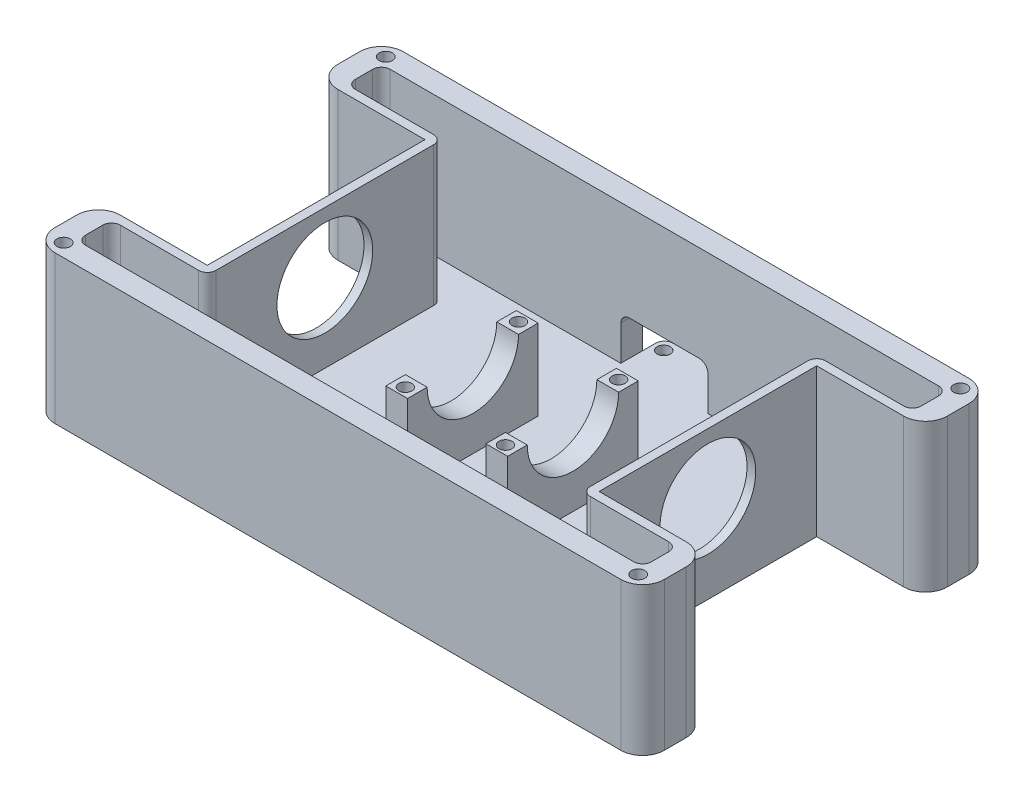
SolidWorks part; units mm, degrees
ref_plane "Front Plane" through (0, 0, 0) normal (0, 0, 1) x (1, 0, 0)
ref_plane "Top Plane" through (0, 0, 0) normal (0, 1, 0) x (1, 0, 0)
ref_plane "Right Plane" through (0, 0, 0) normal (1, 0, 0) x (0, 0, -1)
sketch "Sketch1" plane through (0, 0, 0) normal (0, 1, 0) x (1, 0, 0)
  line L5 (-88.9, 50.8) -> (88.9, 50.8)
  line L6 (-88.9, 50.8) -> (-88.9, -50.8)
  line L7 (-88.9, -50.8) -> (88.9, -50.8)
  line L8 (88.9, 50.8) -> (88.9, -50.8)
  line L9 (-88.9, 50.8) -> (88.9, -50.8) construction
  line L10 (-88.9, -50.8) -> (88.9, 50.8) construction
  point P0 (0, 0)
  point P1 (0, 0)
  dimension "D1" = 177.8
  dimension "D2" = 101.6
extrude "Boss-Extrude1" add sketch "Sketch1" along normal blind 2.54
sketch "Sketch2" plane through (0, 2.54, 0) normal (0, 1, 0) x (1, 0, 0)
  line L0 (0, 50.8) -> (0, 11.3567) construction
  line L1 (-82.55, 31.75) -> (-57.15, 31.75)
  line L2 (-82.55, 31.75) -> (-82.55, -31.75)
  line L3 (-82.55, -31.75) -> (-57.15, -31.75)
  line L4 (-57.15, 31.75) -> (-57.15, -31.75)
  line L5 (88.9, 50.8) -> (-88.9, 50.8) construction
  line L6 (-88.9, 50.8) -> (-88.9, -50.8) construction
  line L7 (-88.9, -50.8) -> (88.9, -50.8) construction
  line L8 (82.55, -31.75) -> (57.15, -31.75)
  line L9 (82.55, 31.75) -> (82.55, -31.75)
  line L10 (82.55, 31.75) -> (57.15, 31.75)
  line L11 (57.15, 31.75) -> (57.15, -31.75)
  dimension "D1" = 6.35
  dimension "D2" = 25.4
  dimension "D3" = 63.5
  dimension "D4" = 19.05
extrude "Cut-Extrude1" cut sketch "Sketch2" against normal blind 2.54
sketch "Sketch3" plane through (0, 2.54, 0) normal (0, 1, 0) x (1, 0, 0)
  line L51 (-82.55, -44.45) -> (82.55, -44.45)
  line L52 (82.55, -44.45) -> (82.55, 44.45)
  line L53 (82.55, 44.45) -> (-82.55, 44.45)
  line L54 (-82.55, 44.45) -> (-82.55, -44.45)
  line L61 (-88.9, 50.8) -> (-88.9, -50.8)
  line L62 (88.9, -50.8) -> (88.9, 50.8)
  line L63 (-88.9, -50.8) -> (88.9, -50.8)
  line L64 (88.9, 50.8) -> (-88.9, 50.8)
  line L65 (-88.9, 50.8) -> (-88.9, -50.8)
  line L66 (88.9, -50.8) -> (88.9, 50.8)
  line L70 (-88.9, -50.8) -> (88.9, -50.8)
  line L71 (88.9, 50.8) -> (-88.9, 50.8)
  dimension "D1" = 0
  dimension "D2" = 6.35
extrude "Boss-Extrude2" add sketch "Sketch3" along normal blind 40.64
sketch "Sketch7" plane through (0, 2.54, 0) normal (0, 1, 0) x (1, 0, 0)
  line L0 (82.55, -44.45) -> (82.55, -31.75) construction
  line L1 (54.61, 34.29) -> (82.55, 34.29)
  line L2 (54.61, 34.29) -> (54.61, -34.29)
  line L3 (54.61, -34.29) -> (82.55, -34.29)
  line L4 (82.55, 34.29) -> (82.55, -34.29)
  line L5 (-82.55, 44.45) -> (-82.55, 31.75) construction
  line L6 (-82.55, 34.29) -> (-54.61, 34.29)
  line L7 (-82.55, 34.29) -> (-82.55, -34.29)
  line L8 (-82.55, -34.29) -> (-54.61, -34.29)
  line L9 (-54.61, 34.29) -> (-54.61, -34.29)
  line L11 (-57.15, 31.75) -> (-82.55, 31.75)
  line L12 (-57.15, 31.75) -> (-57.15, -31.75)
  line L13 (-57.15, -31.75) -> (-82.55, -31.75)
  line L14 (-82.55, 31.75) -> (-82.55, -31.75)
  line L15 (57.15, 31.75) -> (82.55, 31.75)
  line L16 (57.15, 31.75) -> (57.15, -31.75)
  line L17 (57.15, -31.75) -> (82.55, -31.75)
  line L18 (82.55, 31.75) -> (82.55, -31.75)
  point P23 (-69.85, 31.75)
  line M12 (-57.15, -31.75) -> (-82.55, -31.75)
  line M13 (-82.55, -31.75) -> (-82.55, -44.45)
  line M15 (82.55, -44.45) -> (82.55, -31.75)
  line M16 (82.55, -31.75) -> (57.15, -31.75)
  line M17 (57.15, -31.75) -> (57.15, 31.75)
  line M18 (57.15, 31.75) -> (82.55, 31.75)
  line M19 (82.55, 31.75) -> (82.55, 44.45)
  line M21 (-82.55, 44.45) -> (-82.55, 31.75)
  line M22 (-82.55, 31.75) -> (-57.15, 31.75)
  line M23 (-57.15, 31.75) -> (-57.15, -31.75)
  dimension "D1" = 2.54
  dimension "D2" = 2.54
  dimension "D3" = 2.54
  dimension "D4" = 2.54
  dimension "D5" = 2.54
  dimension "D6" = 2.54
  dimension "D7" = 63.5
extrude "Boss-Extrude3" add sketch "Sketch7" along normal blind 40.64 contours L9 L6 L8 M21 M22 M23 M12 M13 | L2 L3 L1 M15 M16 M17 M18 M19
sketch "Sketch8" plane through (0, 2.54, 0) normal (0, 1, 0) x (1, 0, 0)
  line L0 (-57.15, 31.75) -> (-57.15, -31.75) construction
  line L1 (-17.78, 19.05) -> (-11.43, 19.05)
  line L2 (-17.78, 19.05) -> (-17.78, -19.05)
  line L3 (-17.78, -19.05) -> (-11.43, -19.05)
  line L4 (-11.43, 19.05) -> (-11.43, -19.05)
  line L5 (-17.78, 19.05) -> (-11.43, -19.05) construction
  line L6 (-17.78, -19.05) -> (-11.43, 19.05) construction
  line L7 (0, 0) -> (0, 19.6064) construction
  line L8 (-88.9, -50.8) -> (88.9, -50.8) construction
  point P0 (-14.605, 0)
  dimension "D1" = 6.35
  dimension "D2" = 45.72
  dimension "D3" = 38.1
  dimension "D4" = 50.8
extrude "Boss-Extrude4" add sketch "Sketch8" along normal blind 10.16
sketch "Sketch9" plane through (-11.43, 0, 0) normal (1, 0, 0) x (0, 0, -1)
  line L0 (-19.05, 12.7) -> (19.05, 12.7) construction
  line L2 (-19.05, 12.7) -> (19.05, 12.7)
  line L3 (-19.05, 12.7) -> (-19.05, 26.035)
  line L5 (19.05, 12.7) -> (19.05, 26.035)
  line L6 (19.05, 12.7) -> (19.05, 2.54) construction
  line L7 (-13.335, 26.035) -> (-19.05, 26.035)
  line L8 (13.335, 26.035) -> (19.05, 26.035)
  arc A0 (-13.335, 26.035) -> (13.335, 26.035) centre (0, 26.035) ccw
  dimension "D1" = 26.67
extrude "Boss-Extrude5" add sketch "Sketch9" against normal up to surface (6.35 mm away) up to face at (-17.78, 7.62, 0)
sketch "Sketch10" plane through (0, 43.18, 0) normal (0, 1, 0) x (1, 0, 0)
  line L0 (-88.9, 50.8) -> (-88.9, -50.8) construction
  line L1 (-82.55, 31.75) -> (-88.9, 31.75)
  line L2 (-82.55, 31.75) -> (-82.55, -31.75)
  line L3 (-82.55, -31.75) -> (-88.9, -31.75)
  line L4 (-88.9, 31.75) -> (-88.9, -31.75)
  line L5 (88.9, -50.8) -> (88.9, 50.8) construction
  line L6 (82.55, 31.75) -> (88.9, 31.75)
  line L7 (82.55, 31.75) -> (82.55, -31.75)
  line L8 (82.55, -31.75) -> (88.9, -31.75)
  line L9 (88.9, 31.75) -> (88.9, -31.75)
extrude "Cut-Extrude2" cut sketch "Sketch10" against normal blind 107.696
mirror "Mirror1" about plane through (0, 0, 0) normal (1, 0, 0) of "Boss-Extrude5", "Boss-Extrude4"
sketch "Sketch11" plane through (54.61, 0, 0) normal (-1, 0, 0) x (0, 0, 1)
  line L0 (31.75, 0) -> (-31.75, 0) construction
  circle A0 centre (0, 25.4) radius 13.97
  dimension "D1" = 27.94
  dimension "D2" = 25.4
extrude "Cut-Extrude5" cut sketch "Sketch11" against normal blind 2.54
mirror "Mirror2" about plane through (0, 0, 0) normal (1, 0, 0) of "Cut-Extrude5"
ref_plane "Plane1" through (-88.9, 0, -50.8) normal (0, -1, 0) x (-1, 0, 0)
fillet "Fillet1" radius 6.35 8 edges at (-88.9, 21.59, 31.75) (-88.9, 21.59, -31.75) (88.9, 21.59, -31.75) (88.9, 21.59, 31.75) (88.9, 21.59, 50.8) (-88.9, 21.59, 50.8) (-88.9, 21.59, -50.8) (88.9, 21.59, -50.8)
fillet "Fillet2" radius 2.54 12 edges at (82.55, 22.86, -34.29) (-82.55, 22.86, 44.45) (82.55, 22.86, 44.45) (82.55, 22.86, -44.45) (-82.55, 22.86, -44.45) (-54.61, 22.86, 34.29) (-54.61, 22.86, -34.29) (-82.55, 22.86, -34.29) (-82.55, 22.86, 34.29) (54.61, 22.86, -34.29) (54.61, 22.86, 34.29) (82.55, 22.86, 34.29)
sketch "Sketch14" plane through (0, 2.54, 0) normal (0, 1, 0) x (1, 0, 0)
  line L0 (82.55, 50.8) -> (-82.55, 50.8) construction
  line L1 (-12.7, 57.15) -> (12.7, 57.15)
  line L2 (-12.7, 57.15) -> (-12.7, 50.8)
  line L3 (-12.7, 50.8) -> (12.7, 50.8)
  line L4 (12.7, 57.15) -> (12.7, 50.8)
  dimension "D1" = 25.4
  dimension "D2" = 6.35
  dimension "D3" = 12.7
extrude "Boss-Extrude6" add sketch "Sketch14" against normal up to surface (2.54 mm away) contours L4 L1 L2 L3 up to face at (0, 0, 0)
sketch "Sketch15" plane through (0, 2.54, 0) normal (0, 1, 0) x (1, 0, 0)
  line L0 (-12.7, 57.15) -> (-12.7, 50.8) construction
  line L1 (82.55, 50.8) -> (-82.55, 50.8) construction
  line L2 (12.7, 57.15) -> (12.7, 50.8) construction
  circle A0 centre (-9.7, 53.975) radius 1.905
  circle A1 centre (9.7, 53.975) radius 1.905
  dimension "D1" = 3
  dimension "D2" = 3.81
  dimension "D3" = 3.81
  dimension "D4" = 3.175
  dimension "D6" = 3
  dimension "D5" = 3.175
extrude "Cut-Extrude6" cut sketch "Sketch15" against normal blind 8.636
fillet "Fillet3" radius 2.54 2 edges at (-12.7, 1.27, -57.15) (12.7, 1.27, -57.15)
sketch "Sketch16" plane through (0, 43.18, 0) normal (0, 1, 0) x (1, 0, 0)
  line L0 (-88.9, 44.45) -> (-88.9, 38.1) construction
  line L1 (82.55, 50.8) -> (-82.55, 50.8) construction
  circle A0 centre (-83.82, 46.99) radius 1.95
  circle A1 centre (83.82, 46.99) radius 1.95
  circle A2 centre (83.82, -46.99) radius 1.95
  circle A3 centre (-83.82, -46.99) radius 1.95
  dimension "D1" = 3.9
  dimension "D2" = 5.08
  dimension "D3" = 3.81
  dimension "D4" = 2
  dimension "D5" = 2
extrude "Cut-Extrude7" cut sketch "Sketch16" against normal blind 10
sketch "Sketch17" plane through (0, 26.035, 0) normal (0, 1, 0) x (1, 0, 0)
  line L0 (-17.78, 19.05) -> (-11.43, 19.05) construction
  line L1 (-17.78, 19.05) -> (-17.78, 13.335) construction
  circle A0 centre (-14.605, 16.51) radius 1.905
  circle A1 centre (14.605, 16.51) radius 1.905
  circle A2 centre (14.605, -16.51) radius 1.905
  circle A3 centre (-14.605, -16.51) radius 1.905
  dimension "D1" = 3.81
  dimension "D2" = 2.54
  dimension "D3" = 3.175
  dimension "D4" = 2
  dimension "D5" = 2
extrude "Cut-Extrude8" cut sketch "Sketch17" against normal blind 10
sketch "Sketch18" plane through (0, 0, -50.8) normal (0, 0, -1) x (-1, 0, 0)
  line L1 (-12.7, 2.54) -> (12.7, 2.54)
  line L2 (-12.7, 2.54) -> (-12.7, 15.24)
  line L3 (-12.7, 15.24) -> (12.7, 15.24)
  line L4 (12.7, 2.54) -> (12.7, 15.24)
  dimension "D1" = 12.7
extrude "Cut-Extrude9" cut sketch "Sketch18" against normal blind 10
fillet "Fillet4" radius 2.54 2 edges at (12.7, 15.24, -47.625) (-12.7, 15.24, -47.625)
